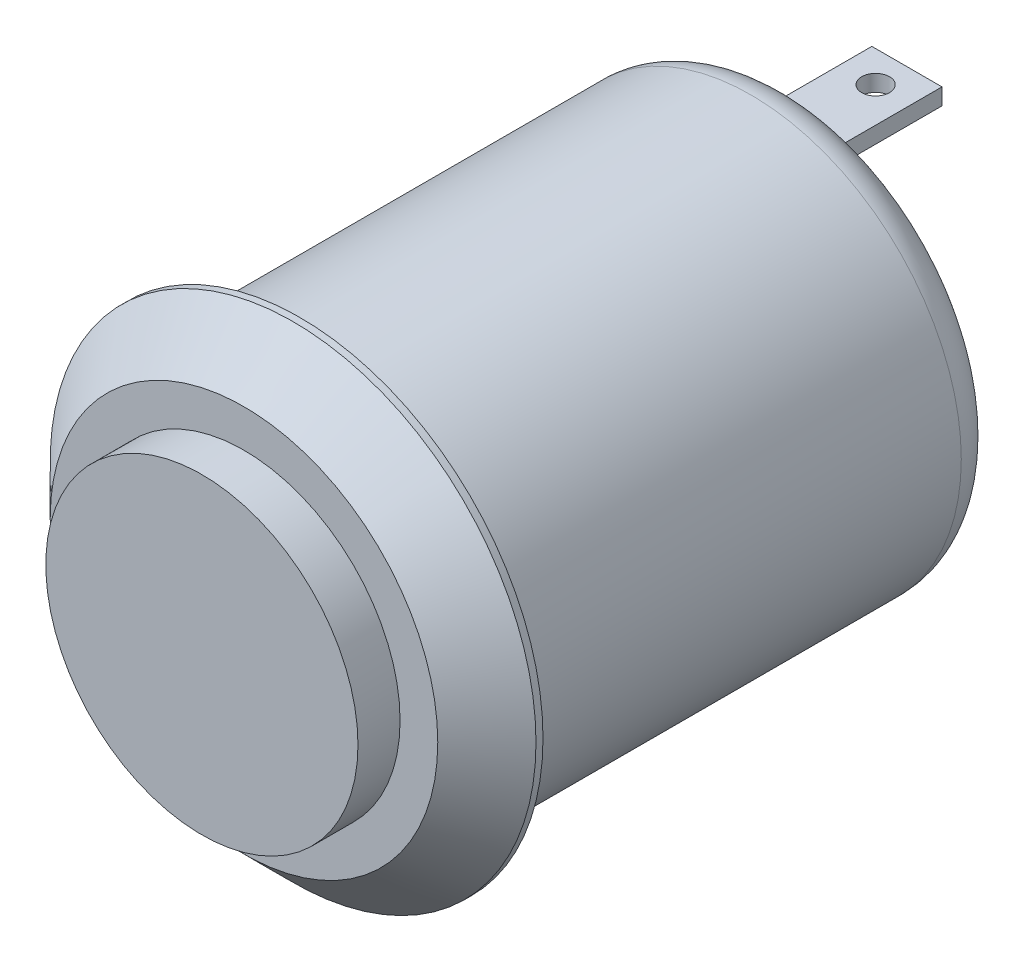
SolidWorks part; units mm, degrees
ref_plane "Front Plane" through (0, 0, 0) normal (0, 0, 1) x (1, 0, 0)
ref_plane "Top Plane" through (0, 0, 0) normal (0, 1, 0) x (1, 0, 0)
ref_plane "Right Plane" through (0, 0, 0) normal (1, 0, 0) x (0, 0, -1)
sketch "Sketch1" plane through (0, 0, 0) normal (0, 0, 1) x (1, 0, 0)
  circle A0 centre (0, 0) radius 6
  dimension "D1" = 12
extrude "Boss-Extrude1" add sketch "Sketch1" against normal blind 14
sketch "Sketch2" plane through (0, 0, 0) normal (0, 0, 1) x (1, 0, 0)
  circle A0 centre (0, 0) radius 6.925
  dimension "D1" = 13.85
extrude "Boss-Extrude2" add sketch "Sketch2" along normal blind 1.6
chamfer "Chamfer1" distance 1.4 1 edges at (6.925, 0, 1.6)
sketch "Sketch3" plane through (0, 0, 1.6) normal (0, 0, 1) x (1, 0, 0)
  circle A0 centre (0, 0) radius 4.45
  dimension "D1" = 8.9
extrude "Boss-Extrude3" add sketch "Sketch3" along normal blind 1.2
fillet "Fillet1" radius 1.15 1 edges at (6, 0, -14)
sketch "Sketch5" plane through (0, 0, -14) normal (0, 0, -1) x (-1, 0, 0)
  line L0 (0, 0) -> (-1.7573, 0) construction
  line L1 (0, 0) -> (0, -0.83) construction
  line L2 (-1, -4) -> (1, -4)
  line L3 (-1, 4) -> (1, 4)
  line L4 (-1, 4) -> (-1, 4.47)
  line L5 (-1, 4.47) -> (1, 4.47)
  line L6 (1, 4) -> (1, 4.47)
  line L7 (-1, 4) -> (1, 4.47) construction
  line L8 (-1, 4.47) -> (1, 4) construction
  line L9 (1, -4) -> (1, -4.47)
  line L10 (-1, -4) -> (-1, -4.47)
  line L11 (-1, -4.47) -> (1, -4.47)
  point P3 (0, 4.235)
  dimension "D1" = 0.47
  dimension "D2" = 4
  dimension "D3" = 2
extrude "Boss-Extrude4" add sketch "Sketch5" along normal blind 3.3
sketch "Sketch6" plane through (0, 4.47, 0) normal (0, 1, 0) x (1, 0, 0)
  circle A0 centre (0, 16.408) radius 0.3954
extrude "Cut-Extrude1" cut sketch "Sketch6" against normal through all
